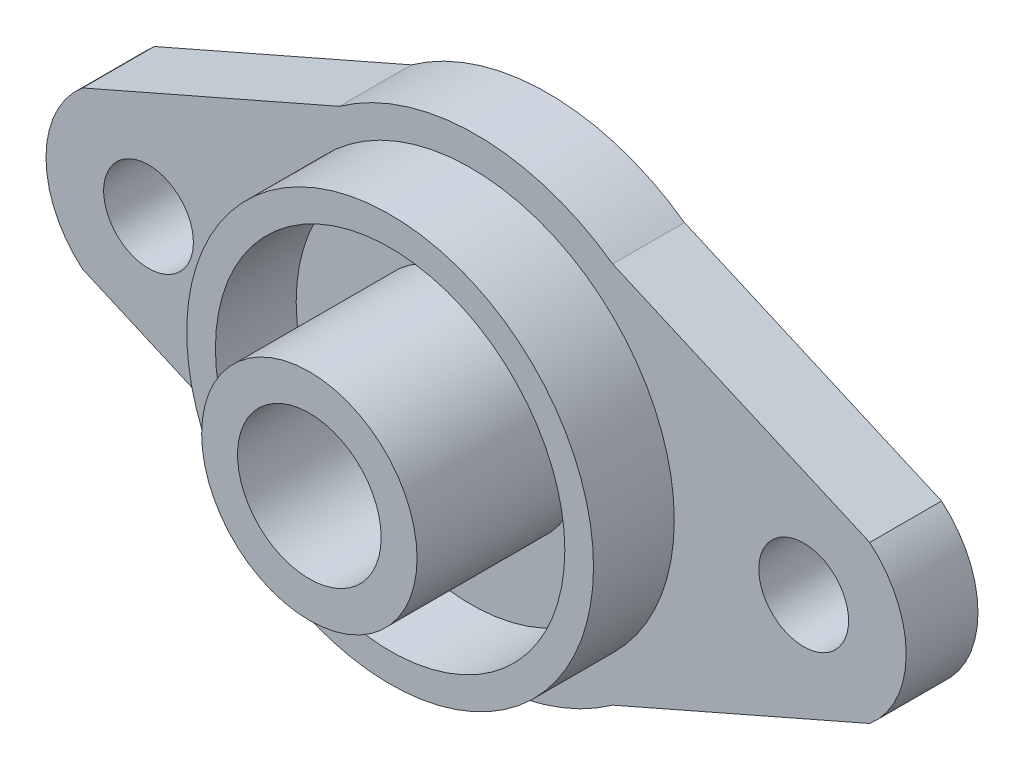
SolidWorks part; units mm, degrees
ref_plane "前视" through (0, 0, 0) normal (0, 0, 1) x (1, 0, 0)
ref_plane "上视" through (0, 0, 0) normal (0, 1, 0) x (1, 0, 0)
ref_plane "右视" through (0, 0, 0) normal (1, 0, 0) x (0, 0, -1)
sketch "草图1" plane through (0, 0, 0) normal (0, 0, 1) x (1, 0, 0)
  line L0 (-94.921, 0) -> (18.25, 0) construction
  line L1 (18.25, 74.4244) -> (18.25, -89.5481) construction
  line L2 (-3.6799, 4.3674) -> (10.6413, 10.6412)
  line L3 (-3.6799, -4.3674) -> (10.6413, -10.6412)
  line L4 (40.1799, -4.3674) -> (25.8587, -10.6412)
  line L5 (40.1799, 4.3674) -> (25.8587, 10.6412)
  arc A0 (-3.6799, -4.3674) -> (-3.6799, 4.3674) centre (0, 0) cw
  arc A1 (10.6413, 10.6412) -> (25.8587, 10.6412) centre (18.25, 0) cw
  arc A2 (10.6413, -10.6412) -> (25.8587, -10.6412) centre (18.25, 0) ccw
  arc A3 (40.1799, -4.3674) -> (40.1799, 4.3674) centre (36.5, 0) ccw
  dimension "D1" = 18.25
extrude "凸台-拉伸1" add sketch "草图1" along normal blind 4
hole_wizard "Ø5.0 (5) 直径孔1" positions "草图3" profile "草图2" hole size "Ø5.0" standard "Gb" end condition through all
sketch "草图3" plane through (0, 0, 4) normal (0, 0, 1) x (1, 0, 0)
  point P0 (0, 0)
  point P3 (36.5, 0)
  dimension "D1" = 36.5
sketch "草图2" plane through (0, 0, 4) normal (1, 0, 0) x (0, -1, 0)
  line L0 (0, 0) -> (0, 4)
  line L1 (0, 4) -> (2.5, 4)
  line L2 (2.5, 4) -> (2.5, 0)
  line L5 (2.5, 0) -> (0, 0)
  line L11 (0, -6.35) -> (0, 107.95) construction
  dimension "通孔孔直径" = 5
  dimension "通孔孔深度" = 4
sketch "草图4" plane through (0, 0, 4) normal (0, 0, 1) x (1, 0, 0)
  circle A0 centre (17.9597, 0) radius 11.3309
extrude "凸台-拉伸2" add sketch "草图4" along normal blind 4.5
sketch "草图5" plane through (0, 0, 8.5) normal (0, 0, 1) x (1, 0, 0)
  circle A0 centre (17.9597, 0) radius 9.7327
extrude "切除-拉伸1" cut sketch "草图5" against normal blind 4.5
sketch "草图6" plane through (0, 0, 4) normal (0, 0, 1) x (1, 0, 0)
  circle A0 centre (17.9597, 0) radius 6
extrude "凸台-拉伸3" add sketch "草图6" along normal blind 9
sketch "草图7" plane through (0, 0, 13) normal (0, 0, 1) x (1, 0, 0)
  circle A0 centre (17.9597, 0) radius 4
extrude "切除-拉伸2" cut sketch "草图7" against normal through all
